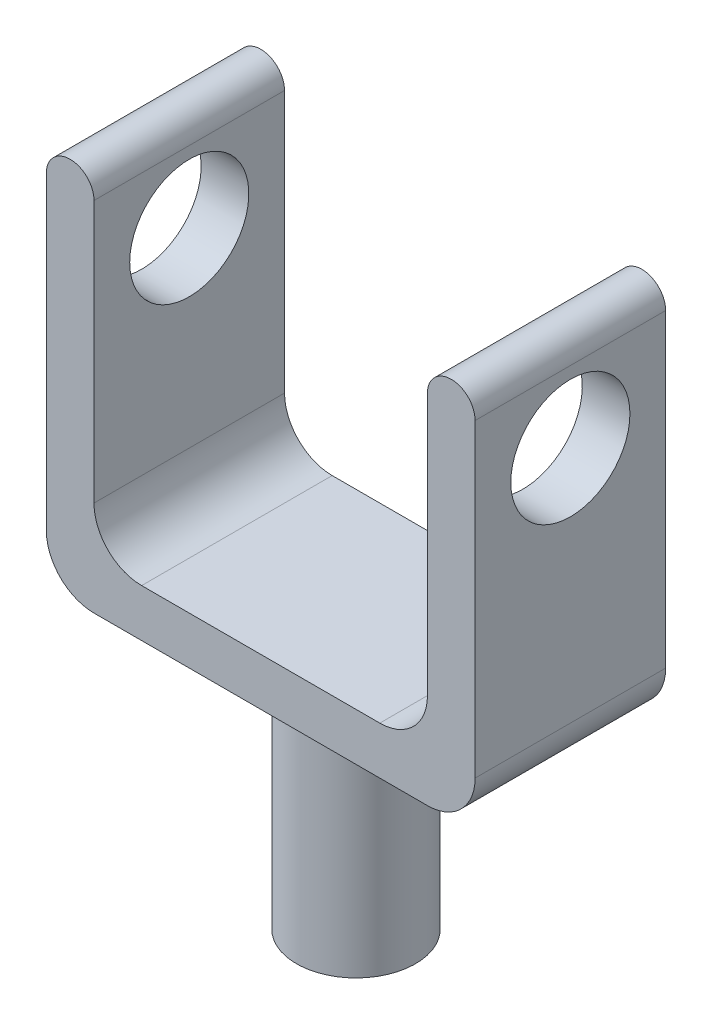
SolidWorks part; units mm, degrees
ref_plane "Front Plane" through (0, 0, 0) normal (0, 0, 1) x (1, 0, 0)
ref_plane "Top Plane" through (0, 0, 0) normal (0, 1, 0) x (1, 0, 0)
ref_plane "Right Plane" through (0, 0, 0) normal (1, 0, 0) x (0, 0, -1)
sketch "Sketch1" plane through (0, 0, 0) normal (0, 0, 1) x (1, 0, 0)
  line L3 (-334.7258, 0) -> (-334.7258, 700) construction
  line L4 (15.2742, 50) -> (15.2742, 700)
  line L6 (-684.7258, 50) -> (15.2742, 50)
  line L9 (-684.7258, 50) -> (-684.7258, 700)
  line L10 (115.2742, -50) -> (115.2742, 700)
  line L11 (-784.7258, -50) -> (115.2742, -50)
  line L12 (-784.7258, -50) -> (-784.7258, 700)
  arc A0 (15.2742, 700) -> (115.2742, 700) centre (65.2742, 700) cw
  arc A1 (-684.7258, 700) -> (-784.7258, 700) centre (-734.7258, 700) ccw
extrude "Boss-Extrude1" add sketch "Sketch1" along normal blind 400
sketch "Sketch3" plane through (0, -50, 0) normal (0, -1, 0) x (1, 0, 0)
  line L0 (-334.7258, 400) -> (-334.7258, 0) construction
  line L1 (-784.7258, 400) -> (115.2742, 400) construction
  line L2 (-784.7258, 0) -> (115.2742, 0) construction
  line L3 (-784.7258, 200) -> (115.2742, 200) construction
  line L4 (-784.7258, 400) -> (-784.7258, 0) construction
  line L5 (115.2742, 400) -> (115.2742, 0) construction
  circle A0 centre (-334.7258, 200) radius 125
  dimension "D1" = 250
extrude "Boss-Extrude2" add sketch "Sketch3" along normal blind 500
fillet "Fillet1" radius 100 4 edges at (115.2742, -50, 200) (-784.7258, -50, 200) (15.2742, 50, 200) (-684.7258, 50, 200)
sketch "Sketch5" plane through (-784.7258, 0, 0) normal (-1, 0, 0) x (0, 0, 1)
  line L0 (200, 750) -> (200, -50) construction
  line L1 (400, 750) -> (0, 750) construction
  line L2 (75, -50) -> (325, -50) construction
  circle A0 centre (200, 550) radius 125
  point P8 (200, 569.776)
  point P9 (200, 573.4823)
  dimension "D1" = 250
  dimension "D2" = 600
extrude "Cut-Extrude1" cut sketch "Sketch5" against normal blind 2046
